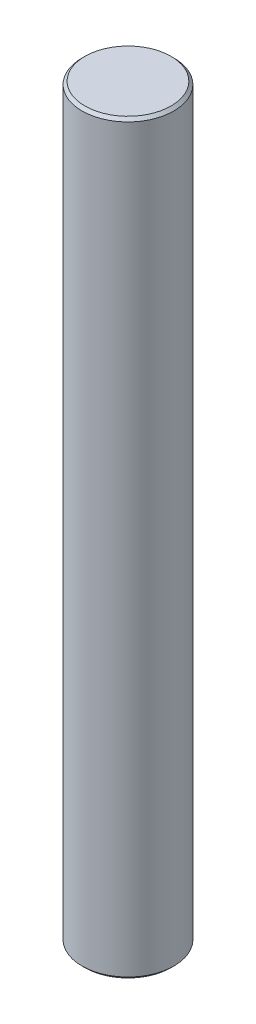
SolidWorks part; units mm, degrees
material "AISI 304"
ref_plane "Front Plane" through (0, 0, 0) normal (0, 0, 1) x (1, 0, 0)
ref_plane "Top Plane" through (0, 0, 0) normal (0, 1, 0) x (1, 0, 0)
ref_plane "Right Plane" through (0, 0, 0) normal (1, 0, 0) x (0, 0, -1)
sketch "Sketch1" plane through (0, 0, 0) normal (0, 1, 0) x (1, 0, 0)
  circle A0 centre (0, 0) radius 4
  dimension "D1" = 8
extrude "Boss-Extrude1" add sketch "Sketch1" along normal blind 65
chamfer "Chamfer1" distance 0.25 angle 45 2 edges at (0, 0, 4) (0, 65, 4)
